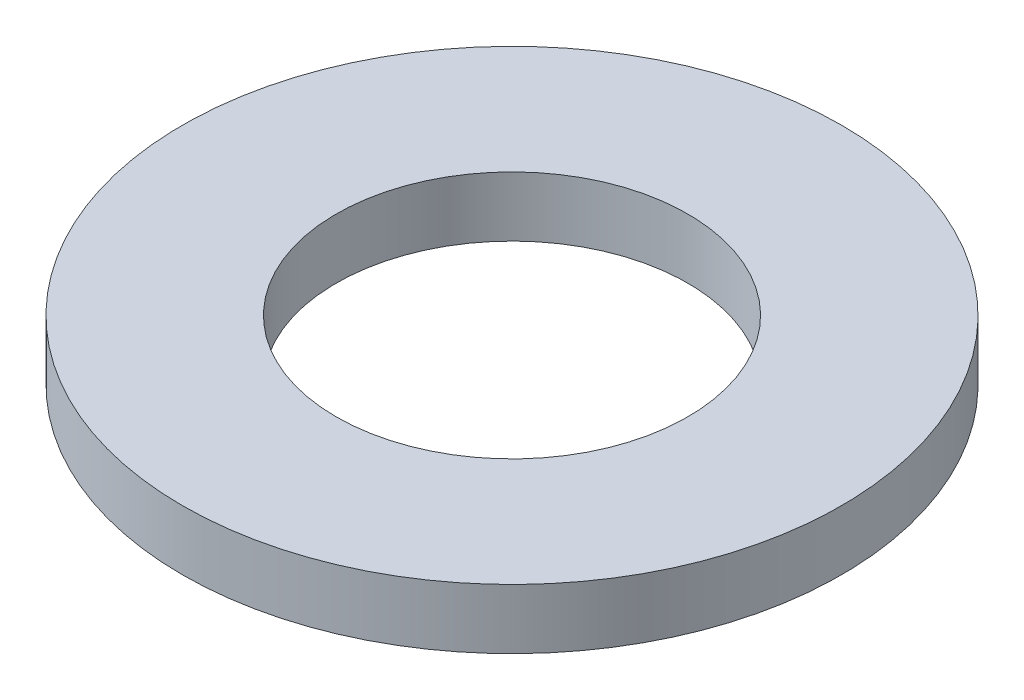
SolidWorks part; units mm, degrees
ref_plane "Front Plane" through (0, 0, 0) normal (0, 0, 1) x (1, 0, 0)
ref_plane "Top Plane" through (0, 0, 0) normal (0, 1, 0) x (1, 0, 0)
ref_plane "Right Plane" through (0, 0, 0) normal (1, 0, 0) x (0, 0, -1)
sketch "Sketch1" plane through (0, 0, 0) normal (0, 1, 0) x (1, 0, 0)
  circle A0 centre (-67.889, 0) radius 8.25
  circle A1 centre (-67.889, 0) radius 4.4
  dimension "D1" = 8.8
  dimension "D2" = 16.5
extrude "Boss-Extrude1" add sketch "Sketch1" along normal blind 1.5
